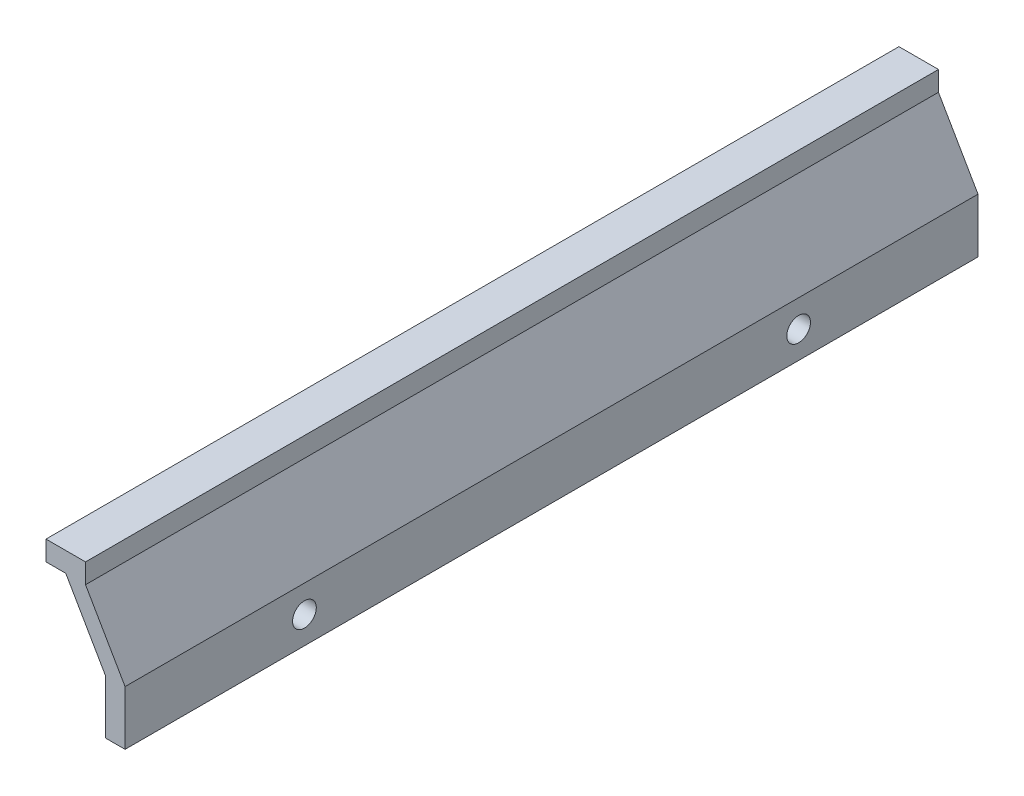
SolidWorks part; units mm, degrees
material "ABS"
ref_plane "正面" through (0, 0, 0) normal (0, 0, 1) x (1, 0, 0)
ref_plane "平面" through (0, 0, 0) normal (0, 1, 0) x (1, 0, 0)
ref_plane "右側面" through (0, 0, 0) normal (1, 0, 0) x (0, 0, -1)
sketch "ｽｹｯﾁ1" plane through (0, 0, 0) normal (0, 0, 1) x (1, 0, 0)
  line L0 (-5, 9.6782) -> (-1, 2.75)
  line L1 (1, -2.75) -> (-1, -2.75)
  line L2 (1, -2.75) -> (1, 2.75)
  line L4 (-1, -2.75) -> (-1, 2.75)
  line L5 (1, -2.75) -> (-1, 2.75) construction
  line L6 (1, 2.75) -> (-1, -2.75) construction
  line L7 (-3, 11.6782) -> (-5, 11.6782)
  line L8 (-3, 11.6782) -> (-3, 9.6782)
  line L11 (-3, 11.6782) -> (-5, 9.6782) construction
  line L12 (-3, 9.6782) -> (-5, 11.6782) construction
  line L13 (-3, 9.6782) -> (1, 2.75)
  line L14 (-5, 9.6782) -> (-7, 9.6782)
  line L15 (-7, 9.6782) -> (-7, 11.6782)
  line L16 (-7, 11.6782) -> (-5, 11.6782)
  point P0 (0, 0)
  point P6 (-4, 10.6782)
  dimension "D1" = 2
  dimension "D2" = 5.5
  dimension "D3" = 8
  dimension "D4" = 150
extrude "ﾎﾞｽ - 押し出し1" add sketch "ｽｹｯﾁ1" along normal blind 86.3
sketch "ｽｹｯﾁ2" plane through (1, 0, 0) normal (1, 0, 0) x (0, 0, -1)
  line L0 (-86.3, 0) -> (0, 0) construction
  line L1 (-86.3, -2.75) -> (-86.3, 2.75) construction
  circle A0 centre (-68.15, 0) radius 1.2
  circle A1 centre (-18.15, 0) radius 1.2
  point P9 (-43.15, 0)
  dimension "D1" = 25
  dimension "D2" = 50
  dimension "D3" = 2.4
  dimension "D4" = 2.4
extrude "ｶｯﾄ - 押し出し1" cut sketch "ｽｹｯﾁ2" against normal through all
